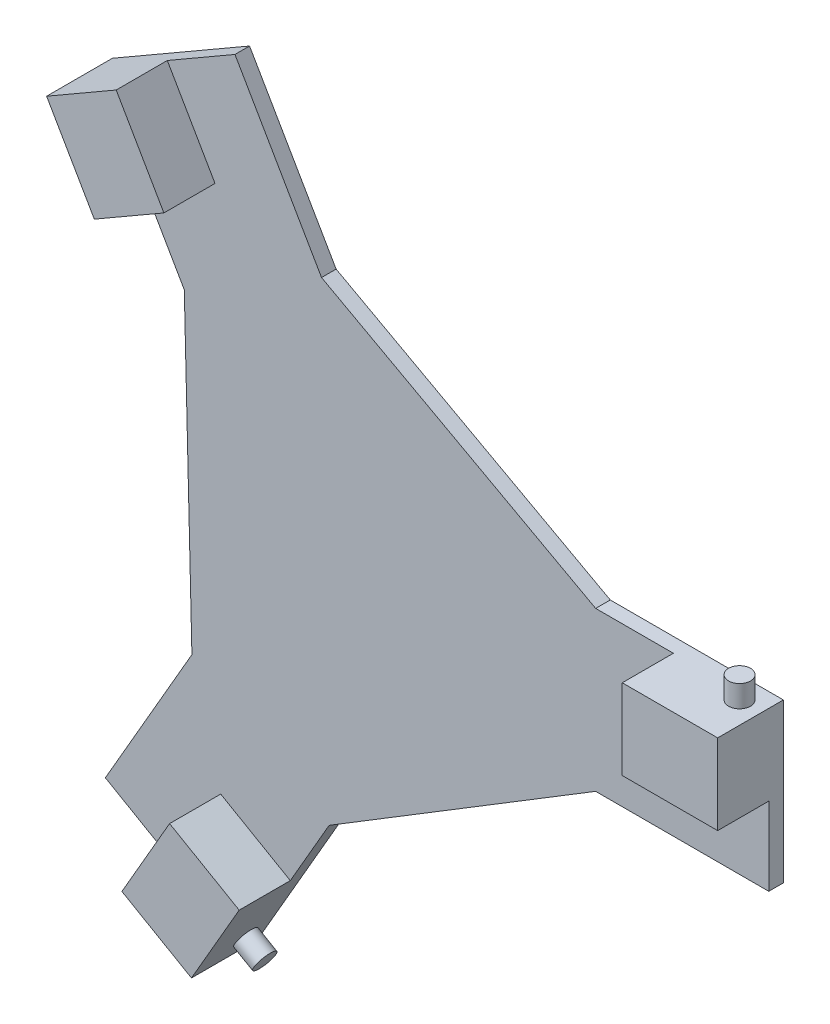
SolidWorks part; units mm, degrees
ref_plane "Front Plane" through (0, 0, 0) normal (0, 0, 1) x (1, 0, 0)
ref_plane "Top Plane" through (0, 0, 0) normal (0, 1, 0) x (1, 0, 0)
ref_plane "Right Plane" through (0, 0, 0) normal (1, 0, 0) x (0, 0, -1)
sketch "Sketch1" plane through (0, 0, 0) normal (0, 0, 1) x (1, 0, 0)
  line L0 (-1000, 0) -> (49000, 0) construction
  line L1 (0, -1000) -> (0, 49000) construction
  line L2 (30.939, 11.4514) -> (54.6455, 11.4514)
  line L3 (54.6455, 11.4514) -> (54.6455, -10.246)
  line L4 (54.6455, -10.246) -> (30.939, -10.246)
  line L5 (-5.5523, -32.5197) -> (-17.4055, -53.0501)
  line L6 (-17.4055, -53.0501) -> (-36.1961, -42.2014)
  line L7 (-36.1961, -42.2014) -> (-24.3428, -21.6709)
  line L8 (-25.3867, 21.0682) -> (-37.24, 41.5987)
  line L9 (-37.24, 41.5987) -> (-18.4494, 52.4474)
  line L10 (-18.4494, 52.4474) -> (-6.5962, 31.917)
  line L11 (-5.5523, -32.5197) -> (30.939, -10.246)
  line L12 (-6.5962, 31.917) -> (30.939, 11.4514)
  line L13 (-25.3867, 21.0682) -> (-24.3428, -21.6709)
  line L14 (-24.3428, -21.6709) -> (-23.7065, -21.4966)
  dimension "D1" = 3
extrude "Boss-Extrude1" add sketch "Sketch1" along normal blind 2 contours L7 L6 L5 L11 L4 L3 L2 L12 L10 L9 L8 L13
sketch "Sketch2" plane through (-9.9172, -5.7257, 0) normal (-0.866, -0.5, 0) x (0, 0, 1)
  line L0 (2, 54.6455) -> (8.8542, 54.6455)
  line L1 (8.8542, 54.6455) -> (8.8542, 41.5808)
  line L2 (8.8542, 41.5808) -> (2, 41.5808)
  line L3 (2, 30.939) -> (2, 54.6455) construction
  line L4 (2, 41.5808) -> (2, 54.6455)
extrude "Boss-Extrude2" add sketch "Sketch2" against normal blind 11
sketch "Sketch3" plane through (0, 0, 2) normal (0, 0, 1) x (1, 0, 0)
  line L0 (-37.24, 41.5987) -> (-27.7137, 47.0987)
  line L1 (-27.7137, 47.0987) -> (-21.1813, 35.7843)
  line L2 (-21.1813, 35.7843) -> (-30.7076, 30.2843)
  line L3 (-30.7076, 30.2843) -> (-37.24, 41.5987)
  line L4 (41.5808, 11.4514) -> (54.6455, 11.4514)
  line L5 (54.6455, 11.4514) -> (54.6455, 0.4514)
  line L6 (54.6455, 0.4514) -> (41.5808, 0.4514)
  line L7 (41.5808, 0.4514) -> (41.5808, 11.4514)
  line L8 (-10.8731, -41.7357) -> (-17.4055, -53.0501)
  line L9 (-17.4055, -53.0501) -> (-26.9318, -47.5501)
  line L10 (-26.9318, -47.5501) -> (-20.3994, -36.2357)
  line L11 (-20.3994, -36.2357) -> (-10.8731, -41.7357)
  dimension "D1" = 3
extrude "Boss-Extrude3" add sketch "Sketch3" along normal blind 7
sketch "Sketch6" plane through (-9.9172, -5.7257, 0) normal (-0.866, -0.5, 0) x (0, 0, 1)
  line L0 (-997.6763, 51.6455) -> (49002.3237, 51.6455) construction
  line L1 (3, -948.8689) -> (3, 49051.1311) construction
  line L2 (9, 54.6455) -> (0, 54.6455) construction
  circle A2 centre (3, 51.6455) radius 1.5
  dimension "D2" = 3
  dimension "D1" = 3
extrude "Boss-Extrude4" add sketch "Sketch6" along normal blind 3
sketch "Sketch7" plane through (9.9172, -5.7257, 0) normal (0.866, -0.5, 0) x (0, 0, -1)
  line L0 (-1002.1562, -51.6455) -> (48997.8438, -51.6455) construction
  line L1 (-3, -1049.3753) -> (-3, 48950.6247) construction
  line L2 (-9, -54.6455) -> (0, -54.6455) construction
  line L3 (0, -30.939) -> (0, -54.6455) construction
  circle A0 centre (-3.0576, -51.6455) radius 1.5
  dimension "D3" = 3
  dimension "D1" = 3
  dimension "D2" = 3
sketch "Sketch8" plane through (0, 11.4514, 0) normal (0, 1, 0) x (1, 0, 0)
  line L0 (-954.9165, -3) -> (49045.0835, -3) construction
  line L2 (36.696, -3) -> (56.1722, -3) construction
  line L3 (51.6455, -1003.7892) -> (51.6455, 48996.2108) construction
  line L4 (54.6455, -9) -> (54.6455, 0) construction
  line L5 (30.939, 0) -> (54.6455, 0) construction
  circle A0 centre (51.6455, -3) radius 1.5
  point P5 (54.6455, -4.5)
  dimension "D3" = 3
  dimension "D1" = 3
  dimension "D2" = 3
extrude "Boss-Extrude5" add sketch "Sketch7" along normal blind 3
extrude "Boss-Extrude6" add sketch "Sketch8" along normal blind 3
